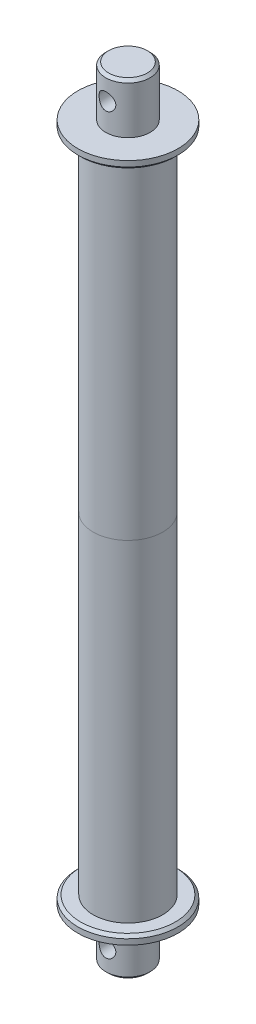
SolidWorks part; units mm, degrees
material "普通碳钢"
ref_plane "前视基准面" through (0, 0, 0) normal (0, 0, 1) x (1, 0, 0)
ref_plane "上视基准面" through (0, 0, 0) normal (0, 1, 0) x (1, 0, 0)
ref_plane "右视基准面" through (0, 0, 0) normal (1, 0, 0) x (0, 0, -1)
sketch "草图1" plane through (0, 0, 0) normal (0, 1, 0) x (1, 0, 0)
  circle A0 centre (0, 0) radius 7.95
  dimension "D1" = 15.9
extrude "凸台-拉伸1" add sketch "草图1" along normal blind 18 contours A0
chamfer "倒角2" distance 1 angle 45 1 edges at (0, 18, 7.95)
sketch "草图9" plane through (0, 0, 0) normal (0, 0, 1) x (1, 0, 0)
  line L0 (0, -8.745) -> (0, 8.745) construction
  line L1 (8.745, 0) -> (-8.745, 0) construction
  circle A0 centre (0, 9.7) radius 3
  dimension "D1" = 9.7
  dimension "D2" = 6
extrude "切除-拉伸2" cut sketch "草图9" against normal through all both and the other way through all
sketch "草图4" plane through (0, 0, 0) normal (0, 1, 0) x (1, 0, 0)
  circle A0 centre (0, 0) radius 18
extrude "凸台-拉伸2" add sketch "草图4" against normal blind 3
chamfer "倒角1" distance 1 angle 45 1 edges at (0, -3, 18)
ref_plane "基准面4" through (0, -3, 0) normal (0, -1, 0) x (-1, 0, 0)
sketch "草图5" plane through (0, -3, 0) normal (0, -1, 0) x (-1, 0, 0)
  circle A0 centre (0, 0) radius 12.5
extrude "凸台-拉伸3" add sketch "草图5" along normal blind 119
ref_plane "基准面5" through (0, -122, 0) normal (0, -1, 0) x (-1, 0, 0)
mirror "镜向3" about plane through (0, -122, 0) normal (0, -1, 0) of bodies 103 108
